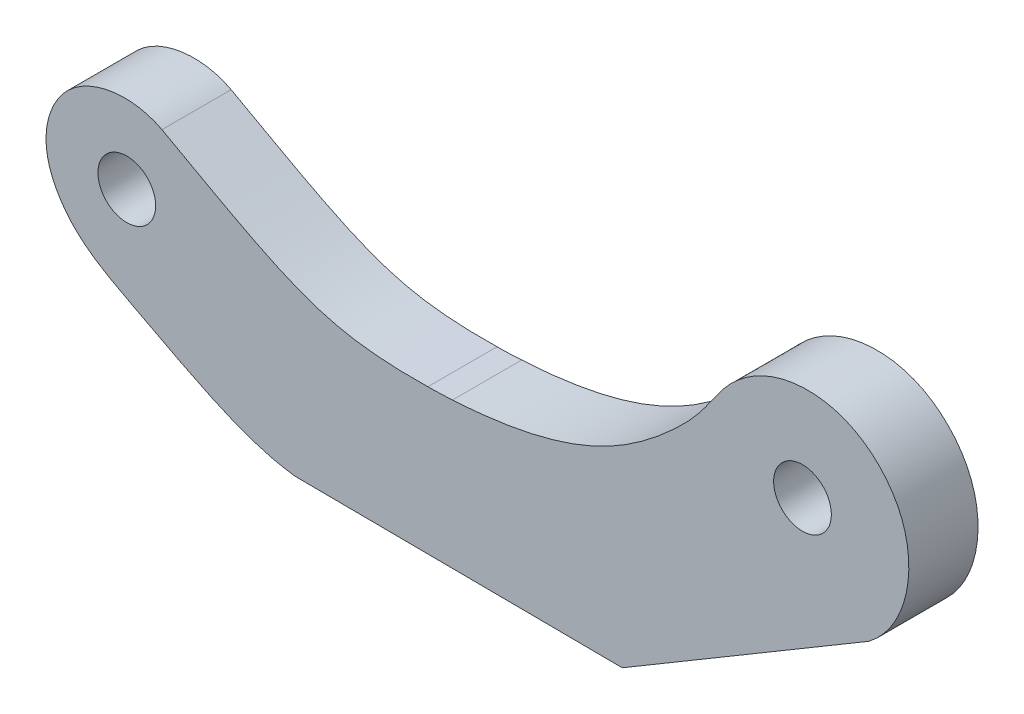
SolidWorks part; units mm, degrees
ref_plane "Piano frontale" through (0, 0, 0) normal (0, 0, 1) x (1, 0, 0)
ref_plane "Piano superiore" through (0, 0, 0) normal (0, 1, 0) x (1, 0, 0)
ref_plane "Piano destro" through (0, 0, 0) normal (1, 0, 0) x (0, 0, -1)
sketch "Schizzo1" plane through (0, 0, 5.05) normal (0, 0, 1) x (1, 0, 0)
  line L2 (-45.8065, 10.1385) -> (-31.2793, 18.7531)
  line L3 (-89.3749, 10.4439) -> (-45.8065, 10.1385)
  line L4 (-45.8065, 10.1385) -> (-31.2793, 18.7531)
  line L5 (-89.3749, 10.4439) -> (-45.8065, 10.1385)
  circle A0 centre (-74.9936, 19.9565) radius 1.7 construction
  circle A1 centre (-35.1891, 24.1136) radius 1.7 construction
  circle A2 centre (-74.9936, 19.9565) radius 1.7
  circle A3 centre (-35.1891, 24.1136) radius 1.7
  ellipse E1 centre (-57.2563, 37.2981) end of major axis (-37.8063, 37.2981) minor radius 18.545 (-57.2563, 18.7531) -> (-55.8032, 18.805) ccw
  ellipse E2 centre (-57.2563, 37.2981) end of major axis (-37.8063, 37.2981) minor radius 18.545 (-57.2563, 18.7531) -> (-55.8032, 18.805) ccw
  spline S0 degree 3 poles (-72.9234, 24.0345) (-74.6668, 24.9728) (-78.609, 24.4333) (-80.3225, 19.661) (-78.2651, 16.1278) (-74.7805, 14.2671) (-70.5898, 12.0499) (-67.2998, 10.5541) (-65.0882, 10.2737) knots 0 0 0 0 0.216025 0.338628 0.486313 0.611907 0.763101 1 1 1 1
  spline S3 degree 3 poles (-55.0226, 4009.8491) (-286.6239, -146.492) (-3.8536, 1.2727) (-32.3004, 29.8584) (-36.6905, 29.9189) (-39.6149, 27.9424) (-41.0325, 25.5521) (-43.2846, 23.2416) (-96.6654, -17.0359) (-333.7984, 323.4745) (2698.1617, -2881.7712) knots -1.172623 -1.172623 -1.172623 -1.172623 0.102244 0.160154 0.214293 0.256273 0.28915 0.319658 0.379342 2.810533 2.810533 2.810533 2.810533 only from (-31.2793, 18.7531) to (-55.8032, 18.805)
  spline S4 degree 3 poles (-935.2546, -3881.5571) (91.537, 254.4662) (-19.0201, -2.943) (-68.3011, 21.4574) (-72.9856, 24.0866) (-76.3153, 25.8751) (-79.7395, 26.2367) (-83.2789, 25.795) (-118.6719, 26.1763) (-148.2825, -57.0088) (1752.9348, -3522.7516) knots -1.324226 -1.324226 -1.324226 -1.324226 0.590345 0.669858 0.735081 0.798411 0.810363 0.866325 0.934004 2.163584 2.163584 2.163584 2.163584 only from (-57.2563, 18.7531) to (-93.0837, 23.8512)
  spline S5 degree 3 poles (-3414.9134, -2195.7578) (207.8494, -9.5775) (-88.4416, 57.6409) (-95.8242, 18.0471) (-95.4062, 15.1624) (-73.837, -15.9305) (88.1127, 92.3456) (89.6607, 4001.5366) knots -0.459028 -0.459028 -0.459028 -0.459028 0.844688 0.876033 0.910905 0.942275 2.154828 2.154828 2.154828 2.154828 only from (-93.0837, 23.8512) to (-89.3749, 10.4439)
  spline S6 degree 3 poles (-31.2793, 18.7531) (-29.098, 20.4037) (-27.9051, 25.4416) (-32.3004, 29.8584) (-36.6905, 29.9189) (-39.6149, 27.9424) (-41.0325, 25.5521) (-43.2846, 23.2416) (-47.7636, 19.8622) (-52.5707, 18.9792) (-55.8032, 18.805) knots 0 0 0 0 0.102244 0.160154 0.214293 0.256273 0.28915 0.319658 0.379342 0.500706 0.500706 0.500706 0.500706
  spline S7 degree 3 poles (-57.2563, 18.7531) (-59.1552, 18.7179) (-63.1278, 18.896) (-68.3011, 21.4574) (-72.9856, 24.0866) (-76.3153, 25.8751) (-79.7395, 26.2367) (-83.2789, 25.795) (-88.2388, 25.8484) (-91.6892, 24.999) (-93.0837, 23.8512) knots 0.518902 0.518902 0.518902 0.518902 0.590345 0.669858 0.735081 0.798411 0.810363 0.866325 0.934004 1 1 1 1
  spline S8 degree 3 poles (-93.0837, 23.8512) (-93.9636, 22.989) (-95.2395, 21.1829) (-95.8242, 18.0471) (-95.4062, 15.1624) (-93.3152, 12.1482) (-91.0893, 10.6926) (-89.3749, 10.4439) knots 0.802408 0.802408 0.802408 0.802408 0.844688 0.876033 0.910905 0.942275 1 1 1 1
  circle M7 centre (-74.9936, 19.9565) radius 1.7
  circle M9 centre (-35.1891, 24.1136) radius 1.7
  line M10 (-45.8065, 10.1385) -> (-31.2793, 18.7531)
  spline M11 degree 3 poles (-31.2793, 18.7531) (-29.098, 20.4037) (-27.9051, 25.4416) (-32.3004, 29.8584) (-36.6905, 29.9189) (-39.6149, 27.9424) (-41.0325, 25.5521) (-43.2846, 23.2416) (-48.1488, 19.5715) (-55.4824, 18.5532) (-63.1278, 18.896) (-68.3011, 21.4574) (-72.9856, 24.0866) (-76.3153, 25.8751) (-79.7395, 26.2367) (-83.2789, 25.795) (-88.2388, 25.8484) (-91.6892, 24.999) (-93.0837, 23.8512) knots 0 0 0 0 0.102244 0.160154 0.214293 0.256273 0.28915 0.319658 0.379342 0.518902 0.590345 0.669858 0.735081 0.798411 0.810363 0.866325 0.934004 1 1 1 1 only from (-31.2793, 18.7531) to (-55.8032, 18.805)
  ellipse M12 centre (-57.2563, 37.2981) end of major axis (-37.8063, 37.2981) minor radius 18.545 (-55.8032, 18.805) -> (-57.2563, 18.7531) cw
  spline M13 degree 3 poles (-31.2793, 18.7531) (-29.098, 20.4037) (-27.9051, 25.4416) (-32.3004, 29.8584) (-36.6905, 29.9189) (-39.6149, 27.9424) (-41.0325, 25.5521) (-43.2846, 23.2416) (-48.1488, 19.5715) (-55.4824, 18.5532) (-63.1278, 18.896) (-68.3011, 21.4574) (-72.9856, 24.0866) (-76.3153, 25.8751) (-79.7395, 26.2367) (-83.2789, 25.795) (-88.2388, 25.8484) (-91.6892, 24.999) (-93.0837, 23.8512) knots 0 0 0 0 0.102244 0.160154 0.214293 0.256273 0.28915 0.319658 0.379342 0.518902 0.590345 0.669858 0.735081 0.798411 0.810363 0.866325 0.934004 1 1 1 1 only from (-57.2563, 18.7531) to (-93.0837, 23.8512)
  dimension "D1" = 0
extrude "Estrusione-Estrusione1" add sketch "Schizzo1" along normal blind 4.077 contours S0 L5 M13 M10 M11 M12 M7 M9
